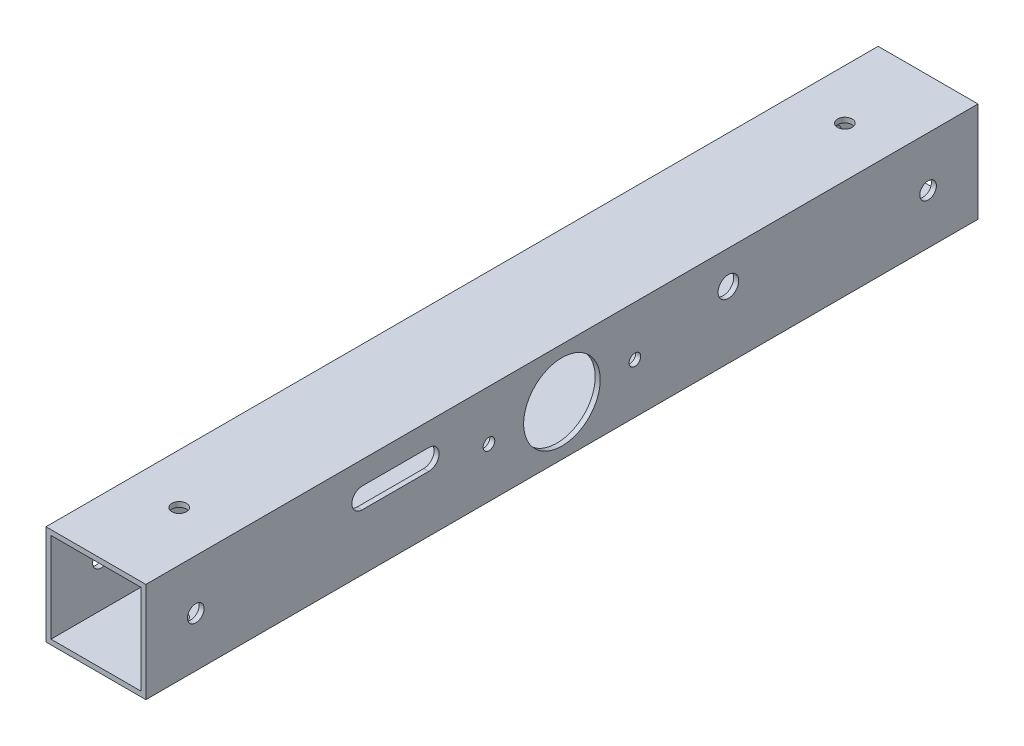
SolidWorks part; units mm, degrees
ref_plane "Front Plane" through (0, 0, 0) normal (0, 0, 1) x (1, 0, 0)
ref_plane "Top Plane" through (0, 0, 0) normal (0, 1, 0) x (1, 0, 0)
ref_plane "Right Plane" through (0, 0, 0) normal (1, 0, 0) x (0, 0, -1)
sketch "Sketch1" plane through (0, 0, 0) normal (0, 0, 1) x (1, 0, 0)
  line L1 (0, 0) -> (30, 0)
  line L2 (0, 0) -> (0, 30)
  line L3 (0, 30) -> (30, 30)
  line L4 (30, 0) -> (30, 30)
  line L5 (1.5, 1.5) -> (28.5, 1.5)
  line L6 (1.5, 1.5) -> (1.5, 28.5)
  line L7 (1.5, 28.5) -> (28.5, 28.5)
  line L8 (28.5, 1.5) -> (28.5, 28.5)
  dimension "D1" = 30
  dimension "D2" = 1.5
  dimension "D3" = 1.5
  dimension "D4" = 1.5
  dimension "D5" = 1.5
  dimension "D6" = 30
extrude "Boss-Extrude1" add sketch "Sketch1" along normal blind 250
sketch "Sketch2" plane through (30, 0, 0) normal (1, 0, 0) x (0, 0, -1)
  line L0 (-250, 0) -> (0, 0) construction
  line L1 (0, 0) -> (0, 30) construction
  line L2 (-185, 23.1) -> (-165, 23.1)
  line L3 (-185, 16.9) -> (-165, 16.9)
  line L4 (-250, 0) -> (-250, 30) construction
  line L5 (-146.92, 15) -> (-125, 15) construction
  line L6 (-103.08, 15) -> (-125, 15) construction
  circle A1 centre (-75, 20) radius 3.1
  arc A2 (-165, 23.1) -> (-165, 16.9) centre (-165, 20) cw
  arc A3 (-185, 23.1) -> (-185, 16.9) centre (-185, 20) ccw
  circle A4 centre (-15, 15) radius 2.5
  circle A5 centre (-235, 15) radius 2.5
  circle A6 centre (-125, 15) radius 11.5
  circle A7 centre (-146.92, 15) radius 1.75
  circle A8 centre (-103.08, 15) radius 1.75
  point P12 (-175, 23.1)
  dimension "D1" = 6.2
  dimension "D2" = 6.2
  dimension "D5" = 100
  dimension "D10" = 5
  dimension "D13" = 5
  dimension "D14" = 23
  dimension "D19" = 3.5
  dimension "D20" = 3.5
  dimension "D3" = 20
  dimension "D4" = 20
  dimension "D6" = 75
  dimension "D7" = 20
  dimension "D8" = 15
  dimension "D9" = 15
  dimension "D11" = 15
  dimension "D12" = 15
  dimension "D15" = 15
  dimension "D16" = 125
  dimension "D17" = 43.84
extrude "Cut-Extrude1" cut sketch "Sketch2" against normal through all
sketch "Sketch3" plane through (0, 30, 0) normal (0, 1, 0) x (1, 0, 0)
  line L0 (0, -250) -> (0, 0) construction
  line L1 (30, 0) -> (0, 0) construction
  line L2 (30, -250) -> (0, -250) construction
  circle A0 centre (15, -25) radius 2.2
  circle A1 centre (15, -225) radius 2.2
  dimension "D1" = 4.4
  dimension "D4" = 4.4
  dimension "D2" = 15
  dimension "D3" = 25
  dimension "D5" = 25
  dimension "D6" = 15
extrude "Cut-Extrude2" cut sketch "Sketch3" against normal through all
